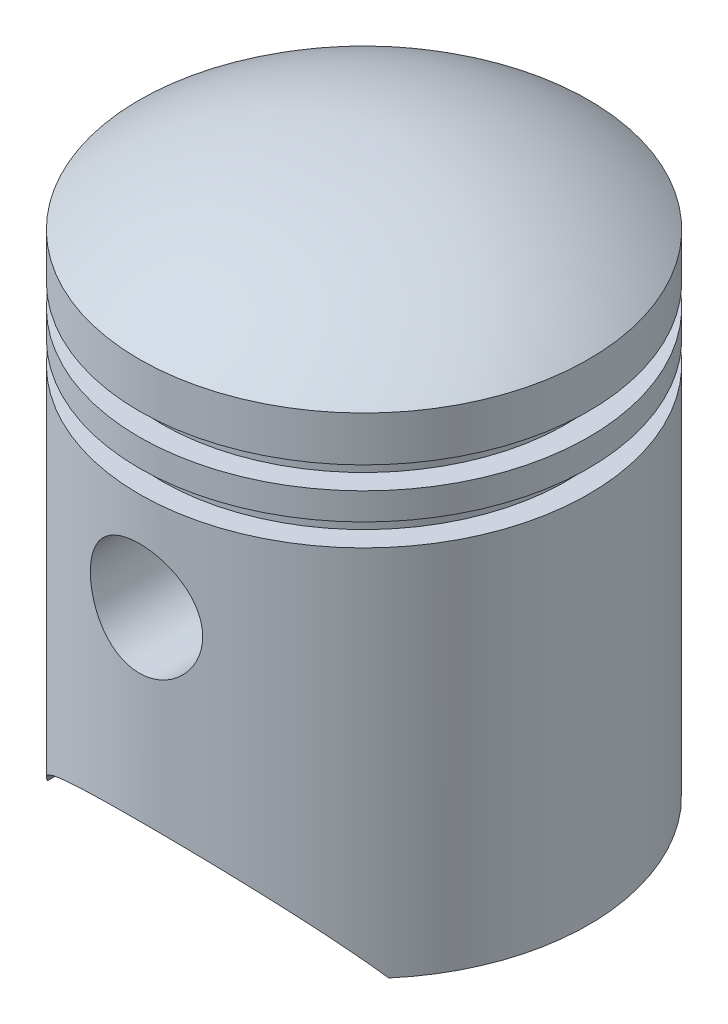
SolidWorks part; units mm, degrees
ref_plane "Front Plane" through (0, 0, 0) normal (0, 0, 1) x (1, 0, 0)
ref_plane "Top Plane" through (0, 0, 0) normal (0, 1, 0) x (1, 0, 0)
ref_plane "Right Plane" through (0, 0, 0) normal (1, 0, 0) x (0, 0, -1)
sketch "Sketch1" plane through (0, 0, 0) normal (0, 0, 1) x (1, 0, 0)
  line L0 (0, 62.5) -> (0, 60.4994)
  line L1 (23, 0) -> (25, 0)
  line L2 (25, 0) -> (25, 41.5)
  line L3 (25, 41.5) -> (22.5, 41.5)
  line L4 (22.5, 41.5) -> (22.5, 44)
  line L5 (22.5, 44) -> (25, 44)
  line L6 (25, 44) -> (25, 47)
  line L7 (25, 47) -> (22.5, 47)
  line L8 (22.5, 47) -> (22.5, 49.5)
  line L9 (22.5, 49.5) -> (25, 49.5)
  line L10 (25, 49.5) -> (25, 54.5)
  line L12 (0, 0) -> (25, 0) construction
  line L13 (23, 0) -> (23, 39.5)
  line L14 (23, 39.5) -> (20.5, 39.5)
  line L15 (20.5, 39.5) -> (20.5, 45.5)
  line L16 (20.5, 45.5) -> (20.5, 45.5)
  line L17 (20.5, 45.5) -> (20.5, 45.5)
  line L18 (20.5, 45.5) -> (20.5, 45.5)
  line L19 (20.5, 45.5) -> (20.5, 51.5)
  line L20 (20.5, 51.5) -> (23, 51.5)
  line L21 (23, 51.5) -> (23, 53.4845)
  line L22 (23, 2) -> (23, 39.5) construction
  line L23 (2, 2) -> (23, 2) construction
  line L24 (2, 60.4985) -> (2, 2) construction
  line L25 (0, 62.5) -> (0, 0) construction
  arc A0 (25, 54.5) -> (0, 62.5) centre (0.9839, 22.5121) ccw
  arc A1 (23, 53.4845) -> (0, 60.4994) centre (0.9839, 22.5121) ccw
  arc A2 (23, 53.4845) -> (2, 60.4985) centre (0.9839, 22.5121) ccw construction
  dimension "D8" = 40
  dimension "D3" = 41.5
  dimension "D4" = 2.5
  dimension "D5" = 2.5
  dimension "D6" = 3
  dimension "D7" = 5
  dimension "D9" = 2
revolve "Revolve1" add sketch "Sketch1" angle 360 about L0
sketch "Sketch2" plane through (0, 0, 0) normal (0, 0, 1) x (1, 0, 0)
  line L0 (19, 0) -> (-19, 0)
  line L1 (-25, 0) -> (25, 0) construction
  line L2 (0, 0) -> (0, 10) construction
  arc A0 (-19, 0) -> (19, 0) centre (0, -13.05) cw
  point P8 (0, 0)
  dimension "D1" = 10
  dimension "D2" = 38
extrude "Cut-Extrude1" cut sketch "Sketch2" against normal mid plane 85 contours A0 L0
sketch "Sketch3" plane through (0, 0, 0) normal (0, 0, 1) x (1, 0, 0)
  line L0 (0, 30.5) -> (0, 62.5) construction
  circle A0 centre (0, 30.5) radius 6.25
  dimension "D2" = 12.5
  dimension "D1" = 32
extrude "Cut-Extrude2" cut sketch "Sketch3" against normal mid plane 85
ref_plane "Plane1" through (0, 0, 12) normal (0, 0, 1) x (1, 0, 0)
sketch "Sketch6" plane through (0, 0, 12) normal (0, 0, 1) x (1, 0, 0)
  circle A0 centre (0, 30.5) radius 6.25 construction
  circle A1 centre (0, 30.5) radius 6.25
  circle A2 centre (0, 30.5) radius 7.25
  dimension "D1" = 14.5
extrude "Boss-Extrude1" add sketch "Sketch6" along normal up to next
mirror "Mirror1" about plane through (0, 0, 0) normal (0, 0, 1) of "Boss-Extrude1"
